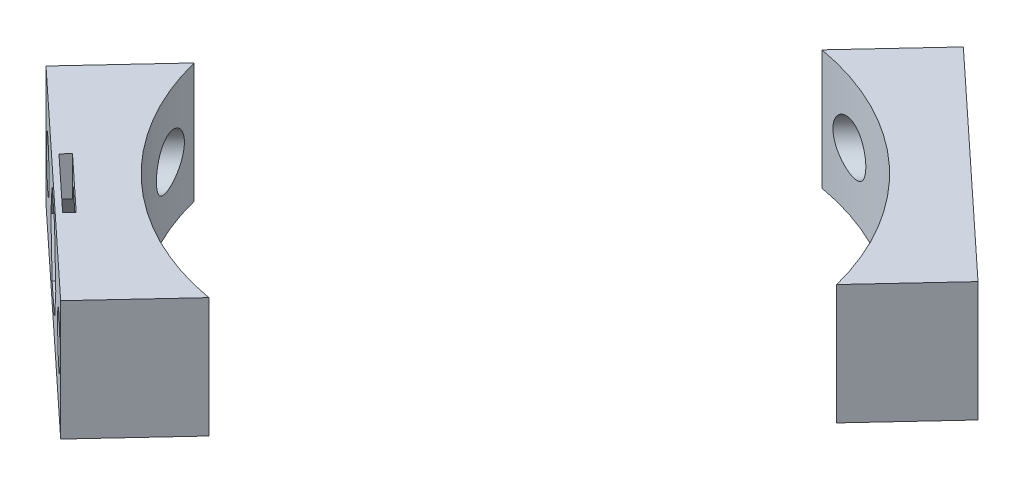
SolidWorks part; units mm, degrees
ref_plane "Front Plane" through (0, 0, 0) normal (0, 0, 1) x (1, 0, 0)
ref_plane "Top Plane" through (0, 0, 0) normal (0, 1, 0) x (1, 0, 0)
ref_plane "Right Plane" through (0, 0, 0) normal (1, 0, 0) x (0, 0, -1)
sketch "Sketch1" plane through (0, 0, 0) normal (0, 1, 0) x (1, 0, 0)
  line L0 (-67.738, -28.7647) -> (-53.364, -13.315)
  line L1 (67.738, 28.7647) -> (53.364, 13.315)
  line L2 (-67.738, -28.7647) -> (-23.8099, -69.6343)
  line L3 (23.8099, 69.6343) -> (67.738, 28.7647)
  line L4 (-45.7739, -49.1995) -> (-37.6, -40.4138) construction
  line L5 (45.7739, 49.1995) -> (37.6, 40.4138) construction
  line L6 (-9.4359, -54.1845) -> (-23.8099, -69.6343)
  line L7 (9.4359, 54.1845) -> (23.8099, 69.6343)
  line L8 (-38.7794, -34.341) -> (-31.458, -41.1526)
  line L9 (-44.8102, -22.4721) -> (-52.1315, -15.6605)
  line L10 (-11.1592, -52.3666) -> (-18.6581, -45.7459)
  line L11 (11.4395, 52.6679) -> (18.7608, 45.8563)
  line L12 (31.458, 41.1526) -> (38.7793, 34.341)
  line L13 (44.1638, 21.7773) -> (51.4851, 14.9657)
  circle A0 centre (0, 0) radius 55 construction
  arc A1 (-53.5264, -13.4895) -> (-9.5983, -54.3591) centre (0, 0) ccw
  arc A2 (53.5264, 13.4895) -> (9.5983, 54.3591) centre (0, 0) ccw
  point P31 (-48.4709, -19.0663)
  point P32 (-35.1187, -37.7468)
  point P33 (-14.9086, -49.0562)
  point P34 (35.1187, 37.7468)
  point P35 (15.1001, 49.2621)
  point P36 (47.8244, 18.3715)
sketch "Sketch2" plane through (0, 0, 0) normal (0, 1, 0) x (1, 0, 0)
  line L0 (23.8099, 69.6343) -> (67.738, 28.7647) construction
  line L1 (9.4359, 54.1845) -> (23.8099, 69.6343) construction
  line L2 (67.738, 28.7647) -> (53.364, 13.315) construction
  line L3 (-67.738, -28.7647) -> (-53.364, -13.315) construction
  line L4 (-9.4359, -54.1845) -> (-23.8099, -69.6343) construction
  line L5 (-67.738, -28.7647) -> (-23.8099, -69.6343) construction
  line L6 (23.8099, 69.6343) -> (67.738, 28.7647)
  line L7 (9.5983, 54.3591) -> (23.8099, 69.6343)
  line L8 (67.738, 28.7647) -> (53.5264, 13.4895)
  line L9 (-67.738, -28.7647) -> (-53.5264, -13.4895)
  line L10 (-9.5983, -54.3591) -> (-23.8099, -69.6343)
  line L11 (-67.738, -28.7647) -> (-23.8099, -69.6343)
  arc A0 (-53.5264, -13.4895) -> (-9.5983, -54.3591) centre (0, 0) ccw construction
  arc A1 (53.5264, 13.4895) -> (9.5983, 54.3591) centre (0, 0) ccw construction
  arc A2 (-53.5264, -13.4895) -> (-9.5983, -54.3591) centre (0, 0) ccw
  arc A3 (53.5264, 13.4895) -> (9.5983, 54.3591) centre (0, 0) ccw
extrude "Boss-Extrude1" add sketch "Sketch2" along normal mid plane 25
sketch "Sketch3" plane through (-45.7739, 0, 49.1995) normal (-0.6812, 0, 0.7321) x (0.7321, 0, 0.6812)
  circle A0 centre (-22.5, 0) radius 5
  circle A1 centre (0, 0) radius 5
  circle A2 centre (22.5, 0) radius 5
  dimension "D1" = 10
extrude "Cut-Extrude1" cut sketch "Sketch3" against normal through all both and the other way through all
sketch "Sketch4" plane through (-45.7739, 0, 49.1995) normal (-0.6812, 0, 0.7321) x (0.7321, 0, 0.6812)
  line L0 (4.9941, 8.65) -> (-4.9941, 8.65)
  line L1 (4.9075, 8.5) -> (-4.9075, 8.5) construction
  line L2 (-4.9075, 8.5) -> (-9.815, 0) construction
  line L3 (-9.815, 0) -> (-4.9075, -8.5) construction
  line L4 (-4.9075, -8.5) -> (4.9075, -8.5) construction
  line L5 (4.9075, -8.5) -> (9.815, 0) construction
  line L6 (9.815, 0) -> (4.9075, 8.5) construction
  line L7 (-4.9941, 8.65) -> (-9.9882, 0)
  line L8 (-9.9882, 0) -> (-4.9941, -8.65)
  line L9 (-4.9941, -8.65) -> (4.9941, -8.65)
  line L10 (4.9941, -8.65) -> (9.9882, 0)
  line L11 (9.9882, 0) -> (4.9941, 8.65)
  circle A0 centre (0, 0) radius 8.5 construction
  dimension "D1" = 17
  dimension "D2" = 0.15
extrude "Cut-Extrude2" cut sketch "Sketch4" against normal blind 9
sketch "Sketch5" plane through (0, 12.5, 0) normal (0, 1, 0) x (1, 0, 0)
  line L0 (-51.1968, -44.0176) -> (-40.2148, -54.2349)
  line L1 (-40.2148, -54.2349) -> (-38.8525, -52.7707)
  line L2 (-38.8525, -52.7707) -> (-49.8345, -42.5533)
  line L3 (-49.8345, -42.5533) -> (-51.1968, -44.0176)
  line L4 (-45.7739, -49.1995) -> (-37.6, -40.4138) construction
  line L5 (-67.738, -28.7647) -> (-23.8099, -69.6343) construction
  point P8 (-44.3435, -47.662)
  dimension "D1" = 2
  dimension "D2" = 0.1
  dimension "D3" = 15
extrude "Cut-Extrude3" cut sketch "Sketch5" against normal through all both and the other way through all
sketch "Sketch6" plane through (-45.7739, 0, 49.1995) normal (-0.6812, 0, 0.7321) x (0.7321, 0, 0.6812)
  line L4 (-30, -12.5) -> (30, -12.5)
  line L5 (30, -12.5) -> (30, 12.5)
  line L6 (30, 12.5) -> (-30, 12.5)
  line L7 (-30, 12.5) -> (-30, -12.5)
  line L8 (-30, -12.5) -> (30, -12.5)
  line L9 (30, -12.5) -> (30, 12.5)
  line L10 (30, 12.5) -> (-30, 12.5)
  line L11 (-30, 12.5) -> (-30, -12.5)
  line L14 (-9.815, 0) -> (-4.9075, -8.5) construction
  line L15 (-4.9075, -8.5) -> (4.9075, -8.5) construction
  line L16 (4.9075, -8.5) -> (9.815, 0) construction
  line L17 (9.815, 0) -> (4.9075, 8.5) construction
  line L18 (4.9075, 8.5) -> (-4.9075, 8.5) construction
  line L19 (-4.9075, 8.5) -> (-9.815, 0) construction
  line L20 (-9.9882, 0) -> (-4.9941, -8.65) construction
  line L21 (-4.9941, -8.65) -> (4.9941, -8.65) construction
  line L22 (4.9941, -8.65) -> (9.9882, 0) construction
  line L23 (9.9882, 0) -> (4.9941, 8.65) construction
  line L24 (4.9941, 8.65) -> (-4.9941, 8.65) construction
  line L25 (-4.9941, 8.65) -> (-9.9882, 0) construction
  line L26 (-9.9882, 0) -> (-4.9941, -8.65)
  line L27 (-4.9941, -8.65) -> (4.9941, -8.65)
  line L28 (4.9941, -8.65) -> (9.9882, 0)
  line L29 (9.9882, 0) -> (4.9941, 8.65)
  line L30 (4.9941, 8.65) -> (-4.9941, 8.65)
  line L31 (-4.9941, 8.65) -> (-9.9882, 0)
  circle A1 centre (22.5, 0) radius 5 construction
  circle A2 centre (-22.5, 0) radius 5 construction
  circle A4 centre (22.5, 0) radius 5
  circle A5 centre (-22.5, 0) radius 5
  dimension "D1" = 0
extrude "Boss-Extrude2" add sketch "Sketch6" along normal blind 1
